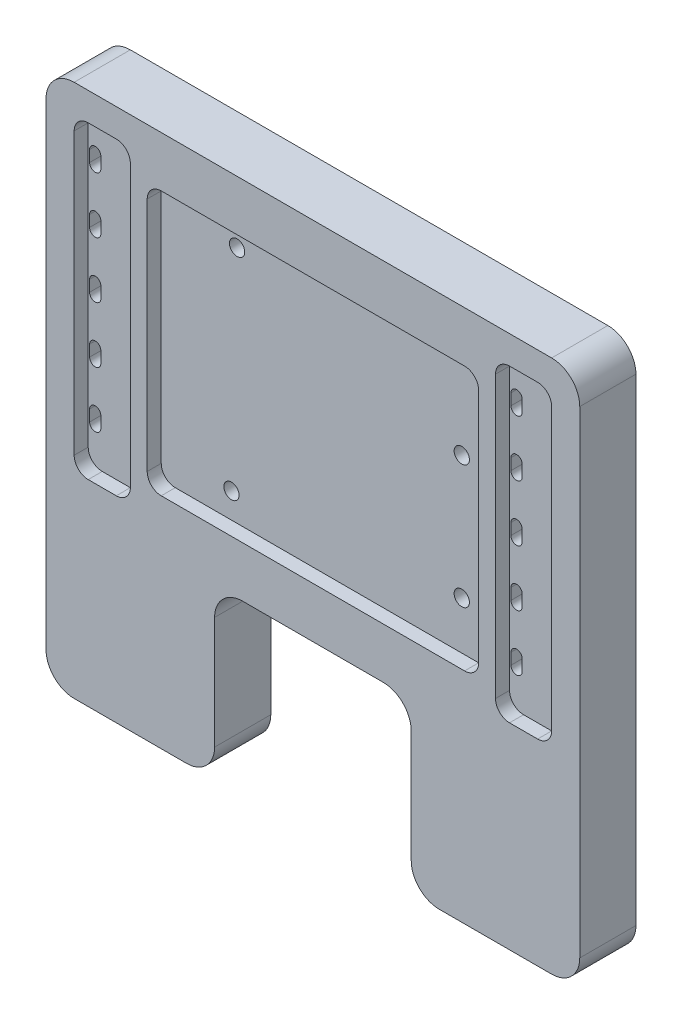
SolidWorks part; units mm, degrees
ref_plane "Front Plane" through (0, 0, 0) normal (0, 0, 1) x (1, 0, 0)
ref_plane "Top Plane" through (0, 0, 0) normal (0, 1, 0) x (1, 0, 0)
ref_plane "Right Plane" through (0, 0, 0) normal (1, 0, 0) x (0, 0, -1)
sketch "Sketch1" plane through (0, 0, 0) normal (0, 0, 1) x (1, 0, 0)
  line L0 (-60.325, 0) -> (60.325, 0)
  line L1 (60.325, 0) -> (60.325, -120.65)
  line L2 (60.325, -120.65) -> (22.225, -120.65)
  line L3 (22.225, -120.65) -> (22.225, -82.55)
  line L4 (22.225, -82.55) -> (-22.225, -82.55)
  line L5 (-22.225, -82.55) -> (-22.225, -120.65)
  line L6 (-22.225, -120.65) -> (-60.325, -120.65)
  line L7 (-60.325, -120.65) -> (-60.325, 0)
  line L8 (0, 0) -> (0, -82.55) construction
  dimension "D1" = 120.65
  dimension "D2" = 38.1
  dimension "D3" = 120.65
  dimension "D4" = 38.1
extrude "Boss-Extrude1" add sketch "Sketch1" along normal blind 12.7
sketch "Sketch2" plane through (0, 0, 12.7) normal (0, 0, 1) x (1, 0, 0)
  line L0 (0, 0) -> (0, -82.55) construction
  line L1 (60.325, 0) -> (-60.325, 0) construction
  line L2 (-22.225, -82.55) -> (22.225, -82.55) construction
  line L3 (-60.325, -41.275) -> (60.325, -41.275) construction
  line L4 (-60.325, 0) -> (-60.325, -120.65) construction
  line L5 (60.325, -120.65) -> (60.325, 0) construction
  line L6 (30.48, -32.385) -> (30.48, -60.325) construction
  line L7 (-34.29, -14.605) -> (34.29, -14.605) construction
  line L8 (-34.29, -14.605) -> (-34.29, -67.945) construction
  line L9 (-34.29, -67.945) -> (34.29, -67.945) construction
  line L10 (34.29, -14.605) -> (34.29, -67.945) construction
  point P12 (0, -41.275)
  point P17 (30.48, -32.385)
  point P18 (0, -67.945)
  point P19 (34.29, -41.275)
  point P20 (-20.32, -17.145)
  point P21 (30.48, -60.325)
  point P22 (-21.59, -65.405)
  dimension "D1" = 68.58
  dimension "D2" = 53.34
  dimension "D3" = 50.8
  dimension "D4" = 1.27
  dimension "D5" = 27.94
  dimension "D6" = 15.24
  dimension "D7" = 5.08
  dimension "D8" = 13.97
  dimension "D9" = 2.54
sketch "Sketch5" plane through (0, 0, 12.7) normal (0, 0, 1) x (1, 0, 0)
  line L0 (53.975, -6.35) -> (53.975, -76.2)
  line L1 (53.975, -76.2) -> (41.275, -76.2)
  line L4 (41.275, -76.2) -> (41.275, -6.35)
  line L5 (41.275, -6.35) -> (53.975, -6.35)
  line L8 (-37.465, -71.12) -> (37.465, -71.12)
  line L9 (37.465, -71.12) -> (37.465, -11.43)
  line L10 (-37.465, -11.43) -> (-37.465, -71.12)
  line L11 (37.465, -11.43) -> (-37.465, -11.43)
  line L12 (-37.465, -71.12) -> (37.465, -71.12)
  line L13 (37.465, -71.12) -> (37.465, -11.43)
  line L14 (-37.465, -11.43) -> (-37.465, -71.12)
  line L15 (37.465, -11.43) -> (-37.465, -11.43)
  line L20 (22.225, -120.65) -> (60.325, -120.65) construction
  line L21 (60.325, -120.65) -> (60.325, 0) construction
  line L22 (60.325, 0) -> (-60.325, 0) construction
  line L24 (0, 0) -> (0, -82.55) construction
  line L25 (-22.225, -82.55) -> (22.225, -82.55) construction
  line L26 (-53.975, -76.2) -> (-41.275, -76.2)
  line L29 (-41.275, -6.35) -> (-53.975, -6.35)
  line L30 (-41.275, -76.2) -> (-41.275, -6.35)
  line L31 (-53.975, -6.35) -> (-53.975, -76.2)
  dimension "D2" = 44.45
  dimension "D3" = 6.35
  dimension "D4" = 6.35
  dimension "D5" = 3.81
  dimension "D1" = 3.175
extrude "Cut-Extrude1" cut sketch "Sketch5" against normal blind 3.175
hole_wizard "#4 Clearance Hole1" positions "Sketch3" profile "Sketch4" hole size "#4" standard "ANSI Inch" end condition through all
sketch "Sketch3" plane through (0, 0, 12.7) normal (0, 0, 1) x (1, 0, 0)
  point P0 (-20.32, -17.145)
  point P3 (-21.59, -65.405)
  point P6 (30.48, -60.325)
  point P9 (30.48, -32.385)
sketch "Sketch4" plane through (-20.32, -17.145, 12.7) normal (1, 0, 0) x (0, -1, 0)
  line L0 (0, 0) -> (0, 12.7)
  line L1 (0, 12.7) -> (1.7272, 12.7)
  line L2 (1.7272, 12.7) -> (1.7272, 0)
  line L5 (1.7272, 0) -> (0, 0)
  line L11 (0, -6.35) -> (0, 107.95) construction
  dimension "Thru Hole Dia." = 3.4544
  dimension "Thru Hole Depth" = 12.7
sketch "Sketch6" plane through (0, 0, 0) normal (0, 0, -1) x (-1, 0, 0)
  line L1 (22.3822, -20.7169) -> (24.4444, -17.145)
  line L2 (24.4444, -17.145) -> (22.3822, -13.5731)
  line L3 (22.3822, -13.5731) -> (18.2578, -13.5731)
  line L4 (18.2578, -13.5731) -> (16.1956, -17.145)
  line L5 (16.1956, -17.145) -> (18.2578, -20.7169)
  line L6 (18.2578, -20.7169) -> (22.3822, -20.7169)
  line L7 (23.6522, -68.9769) -> (25.7144, -65.405)
  line L8 (25.7144, -65.405) -> (23.6522, -61.8331)
  line L9 (23.6522, -61.8331) -> (19.5278, -61.8331)
  line L10 (19.5278, -61.8331) -> (17.4656, -65.405)
  line L11 (17.4656, -65.405) -> (19.5278, -68.9769)
  line L12 (19.5278, -68.9769) -> (23.6522, -68.9769)
  line L13 (-28.4178, -63.8969) -> (-26.3556, -60.325)
  line L14 (-26.3556, -60.325) -> (-28.4178, -56.7531)
  line L15 (-28.4178, -56.7531) -> (-32.5422, -56.7531)
  line L16 (-32.5422, -56.7531) -> (-34.6044, -60.325)
  line L17 (-34.6044, -60.325) -> (-32.5422, -63.8969)
  line L18 (-32.5422, -63.8969) -> (-28.4178, -63.8969)
  line L19 (-28.4178, -35.9569) -> (-26.3556, -32.385)
  line L20 (-26.3556, -32.385) -> (-28.4178, -28.8131)
  line L21 (-28.4178, -28.8131) -> (-32.5422, -28.8131)
  line L22 (-32.5422, -28.8131) -> (-34.6044, -32.385)
  line L23 (-34.6044, -32.385) -> (-32.5422, -35.9569)
  line L24 (-32.5422, -35.9569) -> (-28.4178, -35.9569)
  circle A0 centre (20.32, -17.145) radius 3.5719 construction
  circle A1 centre (21.59, -65.405) radius 3.5719 construction
  circle A2 centre (-30.48, -60.325) radius 3.5719 construction
  circle A3 centre (-30.48, -32.385) radius 3.5719 construction
  dimension "D1" = 7.1437
extrude "Cut-Extrude2" cut sketch "Sketch6" against normal blind 2.3813
sketch "Sketch7" plane through (0, 0, 9.525) normal (0, 0, 1) x (1, 0, 0)
  line L0 (52.3875, -14.605) -> (52.3875, -17.145) construction
  line L1 (53.6575, -14.605) -> (53.6575, -17.145)
  line L2 (51.1175, -14.605) -> (51.1175, -17.145)
  line L3 (53.975, -6.35) -> (41.275, -6.35) construction
  line L5 (52.3875, -27.305) -> (52.3875, -29.845) construction
  line L6 (53.6575, -27.305) -> (53.6575, -29.845)
  line L7 (51.1175, -27.305) -> (51.1175, -29.845)
  line L8 (52.3875, -40.005) -> (52.3875, -42.545) construction
  line L9 (53.6575, -40.005) -> (53.6575, -42.545)
  line L10 (51.1175, -40.005) -> (51.1175, -42.545)
  line L11 (52.3875, -52.705) -> (52.3875, -55.245) construction
  line L12 (53.6575, -52.705) -> (53.6575, -55.245)
  line L13 (51.1175, -52.705) -> (51.1175, -55.245)
  line L14 (52.3875, -65.405) -> (52.3875, -67.945) construction
  line L15 (53.6575, -65.405) -> (53.6575, -67.945)
  line L16 (51.1175, -65.405) -> (51.1175, -67.945)
  line L20 (42.8625, -15.875) -> (52.3875, -15.875) construction
  line L26 (47.625, -6.35) -> (47.625, -76.2) construction
  line L27 (41.275, -76.2) -> (53.975, -76.2) construction
  line L37 (42.8625, -65.405) -> (42.8625, -67.945) construction
  line L38 (41.5925, -65.405) -> (41.5925, -67.945)
  line L39 (44.1325, -65.405) -> (44.1325, -67.945)
  line L40 (42.8625, -52.705) -> (42.8625, -55.245) construction
  line L41 (41.5925, -52.705) -> (41.5925, -55.245)
  line L42 (44.1325, -52.705) -> (44.1325, -55.245)
  line L43 (42.8625, -40.005) -> (42.8625, -42.545) construction
  line L44 (41.5925, -40.005) -> (41.5925, -42.545)
  line L45 (44.1325, -40.005) -> (44.1325, -42.545)
  line L46 (42.8625, -27.305) -> (42.8625, -29.845) construction
  line L47 (41.5925, -27.305) -> (41.5925, -29.845)
  line L48 (44.1325, -27.305) -> (44.1325, -29.845)
  line L49 (42.8625, -14.605) -> (42.8625, -17.145) construction
  line L50 (41.5925, -14.605) -> (41.5925, -17.145)
  line L51 (44.1325, -14.605) -> (44.1325, -17.145)
  line L67 (0, -82.55) -> (0, 0) construction
  line L68 (-22.225, -82.55) -> (22.225, -82.55) construction
  line L69 (60.325, 0) -> (-60.325, 0) construction
  line L70 (-52.3875, -14.605) -> (-52.3875, -17.145) construction
  line L71 (-53.6575, -14.605) -> (-53.6575, -17.145)
  line L72 (-51.1175, -14.605) -> (-51.1175, -17.145)
  line L73 (-52.3875, -27.305) -> (-52.3875, -29.845) construction
  line L74 (-53.6575, -27.305) -> (-53.6575, -29.845)
  line L75 (-51.1175, -27.305) -> (-51.1175, -29.845)
  line L76 (-52.3875, -40.005) -> (-52.3875, -42.545) construction
  line L77 (-53.6575, -40.005) -> (-53.6575, -42.545)
  line L78 (-51.1175, -40.005) -> (-51.1175, -42.545)
  line L79 (-52.3875, -52.705) -> (-52.3875, -55.245) construction
  line L80 (-53.6575, -52.705) -> (-53.6575, -55.245)
  line L81 (-51.1175, -52.705) -> (-51.1175, -55.245)
  line L82 (-52.3875, -65.405) -> (-52.3875, -67.945) construction
  line L83 (-53.6575, -65.405) -> (-53.6575, -67.945)
  line L84 (-51.1175, -65.405) -> (-51.1175, -67.945)
  line L103 (-42.8625, -65.405) -> (-42.8625, -67.945) construction
  line L104 (-41.5925, -65.405) -> (-41.5925, -67.945)
  line L105 (-44.1325, -65.405) -> (-44.1325, -67.945)
  line L106 (-42.8625, -52.705) -> (-42.8625, -55.245) construction
  line L107 (-41.5925, -52.705) -> (-41.5925, -55.245)
  line L108 (-44.1325, -52.705) -> (-44.1325, -55.245)
  line L109 (-42.8625, -40.005) -> (-42.8625, -42.545) construction
  line L110 (-41.5925, -40.005) -> (-41.5925, -42.545)
  line L111 (-44.1325, -40.005) -> (-44.1325, -42.545)
  line L112 (-42.8625, -27.305) -> (-42.8625, -29.845) construction
  line L113 (-41.5925, -27.305) -> (-41.5925, -29.845)
  line L114 (-44.1325, -27.305) -> (-44.1325, -29.845)
  line L115 (-42.8625, -14.605) -> (-42.8625, -17.145) construction
  line L116 (-41.5925, -14.605) -> (-41.5925, -17.145)
  line L117 (-44.1325, -14.605) -> (-44.1325, -17.145)
  line L131 (-47.625, -6.35) -> (-47.625, -76.2) construction
  arc A0 (53.6575, -14.605) -> (51.1175, -14.605) centre (52.3875, -14.605) ccw
  arc A1 (51.1175, -17.145) -> (53.6575, -17.145) centre (52.3875, -17.145) ccw
  arc A2 (53.6575, -27.305) -> (51.1175, -27.305) centre (52.3875, -27.305) ccw
  arc A3 (51.1175, -29.845) -> (53.6575, -29.845) centre (52.3875, -29.845) ccw
  arc A4 (53.6575, -40.005) -> (51.1175, -40.005) centre (52.3875, -40.005) ccw
  arc A5 (51.1175, -42.545) -> (53.6575, -42.545) centre (52.3875, -42.545) ccw
  arc A6 (53.6575, -52.705) -> (51.1175, -52.705) centre (52.3875, -52.705) ccw
  arc A7 (51.1175, -55.245) -> (53.6575, -55.245) centre (52.3875, -55.245) ccw
  arc A8 (53.6575, -65.405) -> (51.1175, -65.405) centre (52.3875, -65.405) ccw
  arc A9 (51.1175, -67.945) -> (53.6575, -67.945) centre (52.3875, -67.945) ccw
  arc A22 (41.5925, -65.405) -> (44.1325, -65.405) centre (42.8625, -65.405) cw
  arc A23 (44.1325, -67.945) -> (41.5925, -67.945) centre (42.8625, -67.945) cw
  arc A24 (41.5925, -52.705) -> (44.1325, -52.705) centre (42.8625, -52.705) cw
  arc A25 (44.1325, -55.245) -> (41.5925, -55.245) centre (42.8625, -55.245) cw
  arc A26 (41.5925, -40.005) -> (44.1325, -40.005) centre (42.8625, -40.005) cw
  arc A27 (44.1325, -42.545) -> (41.5925, -42.545) centre (42.8625, -42.545) cw
  arc A28 (41.5925, -27.305) -> (44.1325, -27.305) centre (42.8625, -27.305) cw
  arc A29 (44.1325, -29.845) -> (41.5925, -29.845) centre (42.8625, -29.845) cw
  arc A30 (41.5925, -14.605) -> (44.1325, -14.605) centre (42.8625, -14.605) cw
  arc A31 (44.1325, -17.145) -> (41.5925, -17.145) centre (42.8625, -17.145) cw
  arc A40 (-53.6575, -14.605) -> (-51.1175, -14.605) centre (-52.3875, -14.605) cw
  arc A41 (-51.1175, -17.145) -> (-53.6575, -17.145) centre (-52.3875, -17.145) cw
  arc A42 (-53.6575, -27.305) -> (-51.1175, -27.305) centre (-52.3875, -27.305) cw
  arc A43 (-51.1175, -29.845) -> (-53.6575, -29.845) centre (-52.3875, -29.845) cw
  arc A44 (-53.6575, -40.005) -> (-51.1175, -40.005) centre (-52.3875, -40.005) cw
  arc A45 (-51.1175, -42.545) -> (-53.6575, -42.545) centre (-52.3875, -42.545) cw
  arc A46 (-53.6575, -52.705) -> (-51.1175, -52.705) centre (-52.3875, -52.705) cw
  arc A47 (-51.1175, -55.245) -> (-53.6575, -55.245) centre (-52.3875, -55.245) cw
  arc A48 (-53.6575, -65.405) -> (-51.1175, -65.405) centre (-52.3875, -65.405) cw
  arc A49 (-51.1175, -67.945) -> (-53.6575, -67.945) centre (-52.3875, -67.945) cw
  arc A62 (-41.5925, -65.405) -> (-44.1325, -65.405) centre (-42.8625, -65.405) ccw
  arc A63 (-44.1325, -67.945) -> (-41.5925, -67.945) centre (-42.8625, -67.945) ccw
  arc A64 (-41.5925, -52.705) -> (-44.1325, -52.705) centre (-42.8625, -52.705) ccw
  arc A65 (-44.1325, -55.245) -> (-41.5925, -55.245) centre (-42.8625, -55.245) ccw
  arc A66 (-41.5925, -40.005) -> (-44.1325, -40.005) centre (-42.8625, -40.005) ccw
  arc A67 (-44.1325, -42.545) -> (-41.5925, -42.545) centre (-42.8625, -42.545) ccw
  arc A68 (-41.5925, -27.305) -> (-44.1325, -27.305) centre (-42.8625, -27.305) ccw
  arc A69 (-44.1325, -29.845) -> (-41.5925, -29.845) centre (-42.8625, -29.845) ccw
  arc A70 (-41.5925, -14.605) -> (-44.1325, -14.605) centre (-42.8625, -14.605) ccw
  arc A71 (-44.1325, -17.145) -> (-41.5925, -17.145) centre (-42.8625, -17.145) ccw
  point P2 (52.3875, -15.875)
  point P15 (52.3875, -28.575)
  point P22 (52.3875, -41.275)
  point P29 (52.3875, -53.975)
  point P36 (52.3875, -66.675)
  point P87 (42.8625, -66.675)
  point P94 (42.8625, -53.975)
  point P101 (42.8625, -41.275)
  point P108 (42.8625, -28.575)
  point P115 (42.8625, -15.875)
  point P162 (-52.3875, -15.875)
  point P169 (-52.3875, -28.575)
  point P176 (-52.3875, -41.275)
  point P183 (-52.3875, -53.975)
  point P190 (-52.3875, -66.675)
  point P239 (-42.8625, -66.675)
  point P246 (-42.8625, -53.975)
  point P253 (-42.8625, -41.275)
  point P260 (-42.8625, -28.575)
  point P267 (-42.8625, -15.875)
  dimension "D2" = 1.27
  dimension "D1" = 2.54
  dimension "D3" = 9.525
  dimension "D5" = 12.7
  dimension "D6" = 9.525
  dimension "D4" = 5
extrude "Cut-Extrude3" cut sketch "Sketch7" against normal through all
fillet "Fillet1" radius 6.35 8 edges at (60.325, 0, 6.35) (-60.325, 0, 6.35) (-60.325, -120.65, 6.35) (-22.225, -120.65, 6.35) (60.325, -120.65, 6.35) (22.225, -120.65, 6.35) (22.225, -82.55, 6.35) (-22.225, -82.55, 6.35)
fillet "Fillet2" radius 3.175 12 edges at (37.465, -71.12, 11.1125) (37.465, -11.43, 11.1125) (-37.465, -11.43, 11.1125) (-37.465, -71.12, 11.1125) (41.275, -6.35, 11.1125) (53.975, -76.2, 11.1125) (-41.275, -6.35, 11.1125) (53.975, -6.35, 11.1125) (-53.975, -6.35, 11.1125) (-53.975, -76.2, 11.1125) (-41.275, -76.2, 11.1125) (41.275, -76.2, 11.1125)
equation "\"D4@Sketch5\"=\"D3@Sketch5\""
